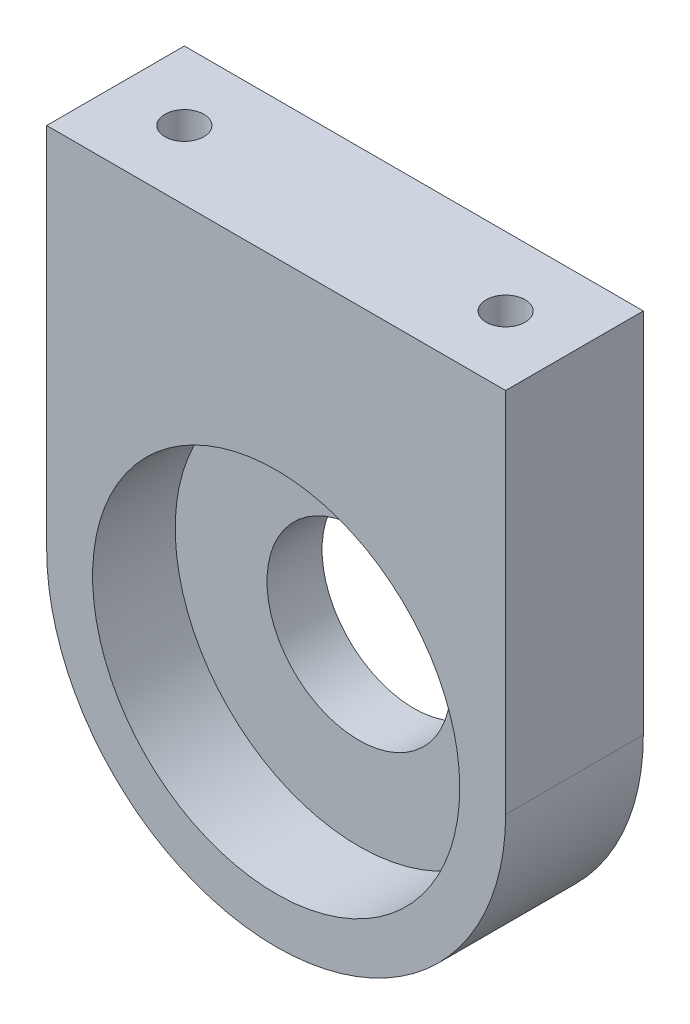
SolidWorks part; units mm, degrees
other "Markup1"
sketch "Sketch6" plane through (50, 80, 15) normal (0.4, 0.515, 0.7581) x (0.8844, 0, -0.4667)
material "Alloy Steel"
ref_plane "Front Plane" through (0, 0, 0) normal (0, 0, 1) x (1, 0, 0)
ref_plane "Top Plane" through (0, 0, 0) normal (0, 1, 0) x (1, 0, 0)
ref_plane "Right Plane" through (0, 0, 0) normal (1, 0, 0) x (0, 0, -1)
sketch "Sketch1" plane through (0, 0, 0) normal (0, 0, 1) x (1, 0, 0)
  line L0 (-50, 80) -> (-50, 0)
  line L1 (55, 0) -> (-55, 0) construction
  line L3 (50, 0) -> (50, 80)
  line L4 (50, 80) -> (-50, 80)
  arc A0 (-50, 0) -> (50, 0) centre (0, 0) ccw
  dimension "D1" = 50
  dimension "D2" = 100
  dimension "D3" = 80
extrude "Boss-Extrude1" add sketch "Sketch1" along normal mid plane 30
sketch "Sketch2" plane through (0, 80, 0) normal (0, 1, 0) x (1, 0, 0)
  line L0 (-55, 0) -> (55, 0) construction
  point P0 (-35, 0)
  point P1 (35, 0)
  dimension "D1" = 35
  dimension "D2" = 35
sketch "Sketch3" plane through (0, 0, 15) normal (0, 0, 1) x (1, 0, 0)
  circle A0 centre (0, 0) radius 20
  dimension "D1" = 40
extrude "Cut-Extrude1" cut sketch "Sketch3" against normal through all
sketch "Sketch4" plane through (0, 0, 15) normal (0, 0, 1) x (1, 0, 0)
  circle A0 centre (0, 0) radius 40
  dimension "D1" = 80
extrude "Cut-Extrude2" cut sketch "Sketch4" against normal blind 18
hole_wizard "M10 Tapped Hole1" positions "3DSketch1" profile "Sketch5" tap size "M10" standard "ISO"
sketch3d "3DSketch1"
  point P0 (-35, 80, 0)
  point P3 (35, 80, 0)
sketch "Sketch5" plane through (-35, 80, 0) normal (1, 0, 0) x (0, 0, 1)
  line L0 (0, 0) -> (0, 28.75)
  line L1 (0, 28.75) -> (4.25, 24.5)
  line L2 (4.25, 24.5) -> (4.25, 0)
  line L5 (4.25, 0) -> (0, 0)
  line L10 (0, 28.75) -> (-4.25, 24.5) construction
  line L11 (0, -6.35) -> (0, 107.95) construction
  dimension "Tap Drill Dia." = 8.5
  dimension "Tap Drill Depth" = 24.5
  dimension "Drill Angle" = 90
cosmetic thread "Hole Thread1" parameters "D1"=22.5, "D2"=10
cosmetic thread "Hole Thread2" parameters "D1"=22.5, "D2"=10
